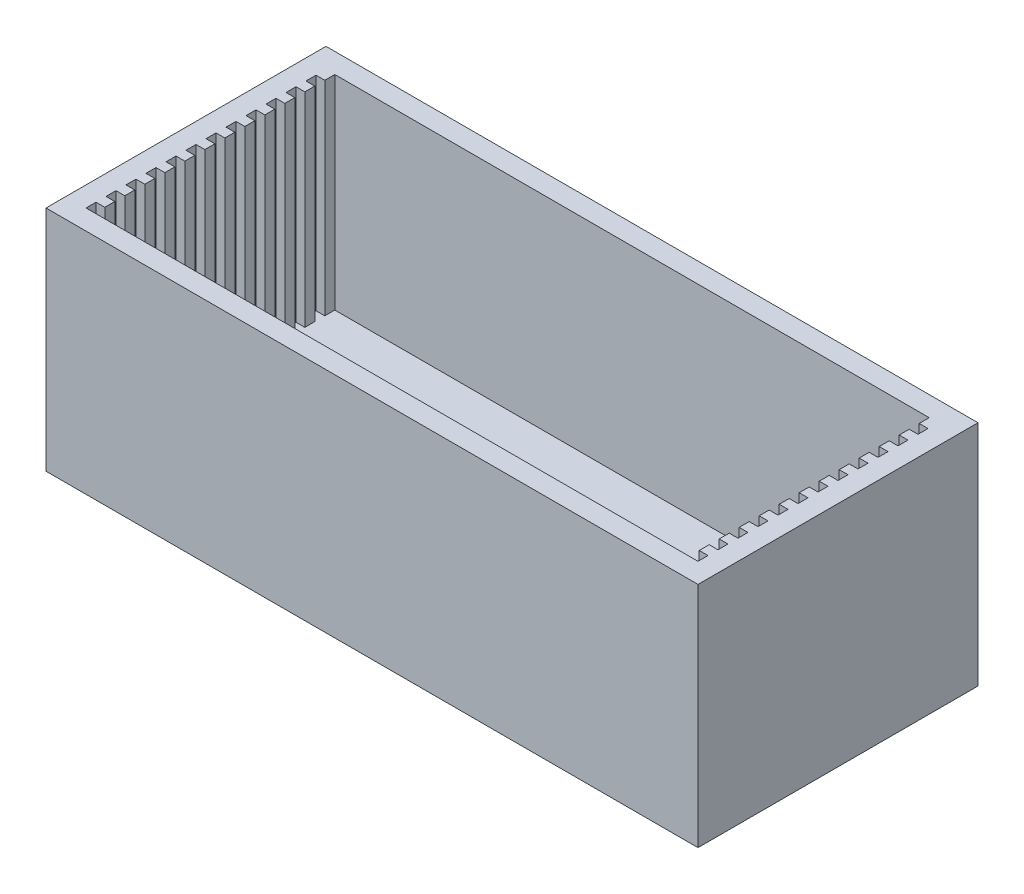
SolidWorks part; units mm, degrees
ref_plane "Front Plane" through (0, 0, 0) normal (0, 0, 1) x (1, 0, 0)
ref_plane "Top Plane" through (0, 0, 0) normal (0, 1, 0) x (1, 0, 0)
ref_plane "Right Plane" through (0, 0, 0) normal (1, 0, 0) x (0, 0, -1)
sketch "Sketch1" plane through (0, 0, 0) normal (0, 1, 0) x (1, 0, 0)
  line L1 (0, 0) -> (81.5, 0)
  line L2 (0, 0) -> (0, 35)
  line L3 (0, 35) -> (81.5, 35)
  line L4 (81.5, 0) -> (81.5, 35)
  dimension "D1" = 35
  dimension "D2" = 81.5
extrude "Boss-Extrude1" add sketch "Sketch1" along normal blind 3
sketch "Sketch2" plane through (0, 3, 0) normal (0, 1, 0) x (1, 0, 0)
  line L0 (40.75, 0) -> (40.75, 35) construction
  line L1 (0, 35) -> (81.5, 35)
  line L2 (0, 35) -> (0, 0)
  line L3 (0, 0) -> (81.5, 0)
  line L4 (81.5, 35) -> (81.5, 0)
  line L6 (2.5, 32.5) -> (2.5, 2.5) construction
  line L9 (2.5, 17.5) -> (0, 17.5) construction
  line L10 (79, 5) -> (79, 6.25)
  line L11 (2.5, 2.5) -> (79, 2.5)
  line L12 (2.5, 2.5) -> (2.5, 3.75)
  line L13 (2.5, 3.75) -> (3.6006, 3.75)
  line L14 (3.6006, 3.75) -> (3.6006, 5)
  line L15 (3.6006, 5) -> (2.5, 5)
  line L16 (2.5, 5) -> (2.5, 6.25)
  line L17 (2.5, 6.25) -> (3.6006, 6.25)
  line L18 (3.6006, 6.25) -> (3.6006, 7.5)
  line L19 (3.6006, 7.5) -> (2.5, 7.5)
  line L20 (2.5, 7.5) -> (2.5, 8.75)
  line L21 (2.5, 8.75) -> (3.6006, 8.75)
  line L22 (3.6006, 8.75) -> (3.6006, 10)
  line L23 (3.6006, 10) -> (2.5, 10)
  line L24 (2.5, 10) -> (2.5, 11.25)
  line L25 (2.5, 11.25) -> (3.6006, 11.25)
  line L26 (3.6006, 11.25) -> (3.6006, 12.5)
  line L27 (3.6006, 12.5) -> (2.5, 12.5)
  line L28 (2.5, 12.5) -> (2.5, 13.75)
  line L29 (2.5, 13.75) -> (3.6006, 13.75)
  line L30 (3.6006, 13.75) -> (3.6006, 15)
  line L31 (3.6006, 15) -> (2.5, 15)
  line L32 (2.5, 15) -> (2.5, 16.25)
  line L33 (2.5, 16.25) -> (3.6006, 16.25)
  line L34 (3.6006, 16.25) -> (3.6006, 17.5)
  line L35 (3.6006, 17.5) -> (2.5, 17.5)
  line L36 (2.5, 17.5) -> (2.5, 18.75)
  line L37 (2.5, 18.75) -> (3.6006, 18.75)
  line L38 (3.6006, 18.75) -> (3.6006, 20)
  line L39 (3.6006, 20) -> (2.5, 20)
  line L40 (2.5, 20) -> (2.5, 21.25)
  line L41 (2.5, 21.25) -> (3.6006, 21.25)
  line L42 (3.6006, 21.25) -> (3.6006, 22.5)
  line L43 (3.6006, 22.5) -> (2.5, 22.5)
  line L44 (2.5, 22.5) -> (2.5, 23.75)
  line L45 (2.5, 23.75) -> (3.6006, 23.75)
  line L46 (3.6006, 23.75) -> (3.6006, 25)
  line L47 (3.6006, 25) -> (2.5, 25)
  line L48 (2.5, 25) -> (2.5, 26.25)
  line L49 (2.5, 26.25) -> (3.6006, 26.25)
  line L50 (3.6006, 26.25) -> (3.6006, 27.5)
  line L51 (3.6006, 27.5) -> (2.5, 27.5)
  line L52 (2.5, 27.5) -> (2.5, 28.75)
  line L53 (2.5, 28.75) -> (3.6006, 28.75)
  line L54 (3.6006, 28.75) -> (3.6006, 30)
  line L55 (3.6006, 30) -> (2.5, 30)
  line L56 (2.5, 30) -> (2.5, 31.25)
  line L57 (2.5, 31.25) -> (3.6006, 31.25)
  line L58 (3.6006, 31.25) -> (3.6006, 32.5)
  line L59 (77.8994, 5) -> (79, 5)
  line L60 (3.6006, 32.5) -> (2.5, 32.5) [skipped]
  line L61 (77.8994, 3.75) -> (77.8994, 5)
  line L62 (79, 3.75) -> (77.8994, 3.75)
  line L63 (79, 2.5) -> (79, 3.75)
  line L64 (77.8994, 6.25) -> (77.8994, 7.5)
  line L65 (79, 6.25) -> (77.8994, 6.25)
  line L66 (77.8994, 31.25) -> (77.8994, 32.5)
  line L67 (79, 31.25) -> (77.8994, 31.25)
  line L68 (79, 30) -> (79, 31.25)
  line L69 (77.8994, 30) -> (79, 30)
  line L70 (77.8994, 28.75) -> (77.8994, 30)
  line L71 (79, 28.75) -> (77.8994, 28.75)
  line L72 (79, 27.5) -> (79, 28.75)
  line L73 (77.8994, 27.5) -> (79, 27.5)
  line L74 (77.8994, 26.25) -> (77.8994, 27.5)
  line L75 (79, 26.25) -> (77.8994, 26.25)
  line L76 (79, 25) -> (79, 26.25)
  line L77 (77.8994, 25) -> (79, 25)
  line L78 (77.8994, 23.75) -> (77.8994, 25)
  line L79 (79, 23.75) -> (77.8994, 23.75)
  line L80 (79, 22.5) -> (79, 23.75)
  line L81 (77.8994, 22.5) -> (79, 22.5)
  line L82 (77.8994, 21.25) -> (77.8994, 22.5)
  line L83 (79, 21.25) -> (77.8994, 21.25)
  line L84 (79, 20) -> (79, 21.25)
  line L85 (77.8994, 20) -> (79, 20)
  line L86 (77.8994, 18.75) -> (77.8994, 20)
  line L87 (79, 18.75) -> (77.8994, 18.75)
  line L88 (79, 17.5) -> (79, 18.75)
  line L89 (77.8994, 17.5) -> (79, 17.5)
  line L90 (77.8994, 16.25) -> (77.8994, 17.5)
  line L91 (79, 16.25) -> (77.8994, 16.25)
  line L92 (79, 15) -> (79, 16.25)
  line L93 (77.8994, 15) -> (79, 15)
  line L94 (77.8994, 13.75) -> (77.8994, 15)
  line L95 (79, 13.75) -> (77.8994, 13.75)
  line L96 (79, 12.5) -> (79, 13.75)
  line L97 (77.8994, 12.5) -> (79, 12.5)
  line L98 (77.8994, 11.25) -> (77.8994, 12.5)
  line L99 (79, 11.25) -> (77.8994, 11.25)
  line L100 (79, 10) -> (79, 11.25)
  line L101 (77.8994, 10) -> (79, 10)
  line L102 (77.8994, 8.75) -> (77.8994, 10)
  line L103 (79, 8.75) -> (77.8994, 8.75)
  line L104 (79, 7.5) -> (79, 8.75)
  line L105 (77.8994, 7.5) -> (79, 7.5)
  line L106 (3.6006, 32.5) -> (77.8994, 32.5)
  point P110 (40.75, 2.5)
  dimension "D1" = 38.25
  dimension "D2" = 30
  dimension "D3" = 1.25
  dimension "D4" = 1.1006
  dimension "D5" = 12
extrude "Boss-Extrude2" add sketch "Sketch2" along normal blind 25.5
